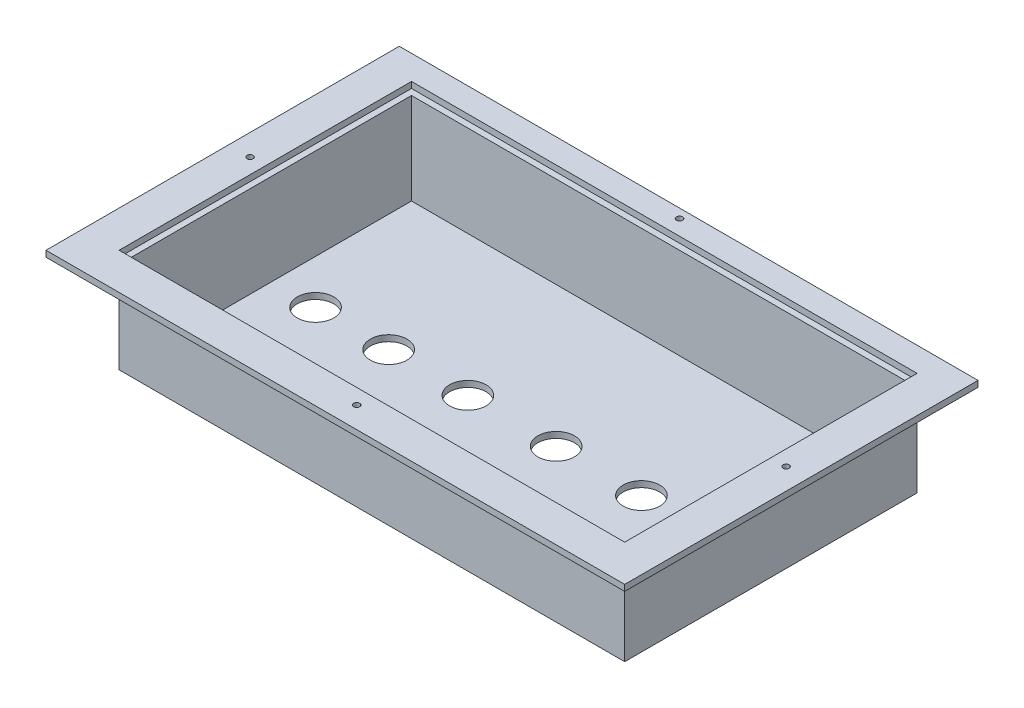
SolidWorks part; units mm, degrees
ref_plane "Front Plane" through (0, 0, 0) normal (0, 0, 1) x (1, 0, 0)
ref_plane "Top Plane" through (0, 0, 0) normal (0, 1, 0) x (1, 0, 0)
ref_plane "Right Plane" through (0, 0, 0) normal (1, 0, 0) x (0, 0, -1)
sketch "Sketch2" plane through (0, 0, 0) normal (0, 1, 0) x (1, 0, 0)
  line L1 (-83, 48) -> (83, 48)
  line L2 (-83, 48) -> (-83, -48)
  line L3 (-83, -48) -> (83, -48)
  line L4 (83, 48) -> (83, -48)
  line L5 (-83, 48) -> (83, -48) construction
  line L6 (-83, -48) -> (83, 48) construction
  line L11 (-81, 46) -> (81, -46) construction
  line L12 (-81, -46) -> (81, 46) construction
  circle A0 centre (-66.5, 0) radius 6
  circle A1 centre (-42.5, 0) radius 6
  circle A2 centre (-16.5, 0) radius 6
  circle A3 centre (12.5, 0) radius 6
  circle A4 centre (40.5, 0) radius 6
  circle A5 centre (67.0043, 4.7099) radius 4.5
  circle A6 centre (67.0043, -8.4422) radius 4.5
  circle A7 centre (67.0043, 22.9699) radius 5.5638
  point P0 (0, 0)
  point P16 (-83, 0)
  point P24 (0, 0)
  dimension "D3" = 16.5
  dimension "D8" = 92
  dimension "D1" = 166
  dimension "D2" = 96
  dimension "D4" = 40.5
  dimension "D5" = 66.5
  dimension "D6" = 95.5
  dimension "D7" = 123.5
  dimension "D9" = 162
extrude "Boss-Extrude1" add sketch "Sketch2" along normal blind 2 contours A0 | A1 | A2 | A3 | A4 | A6 | A7 | L2 L3 L4 L1 | A5
sketch "Sketch3" plane through (0, 2, 0) normal (0, 1, 0) x (1, 0, 0)
  line L1 (-81, 46) -> (81, 46)
  line L2 (-81, 46) -> (-81, -46)
  line L3 (-81, -46) -> (81, -46)
  line L4 (81, 46) -> (81, -46)
  line L5 (-81, 46) -> (81, -46) construction
  line L6 (-81, -46) -> (81, 46) construction
  line L7 (-83, 48) -> (83, 48)
  line L8 (-83, 48) -> (-83, -48)
  line L9 (-83, -48) -> (83, -48)
  line L10 (83, 48) -> (83, -48)
  line L11 (-83, 48) -> (83, -48) construction
  line L12 (-83, -48) -> (83, 48) construction
  point P0 (0, 0)
  point P6 (0, 0)
  dimension "D1" = 162
  dimension "D2" = 92
extrude "Boss-Extrude2" add sketch "Sketch3" along normal blind 30
sketch "Sketch4" plane through (0, 32, 0) normal (0, 1, 0) x (1, 0, 0)
  line L0 (-83, -48) -> (83, -48) construction
  line L1 (-95, 56) -> (95, 56)
  line L2 (-95, 56) -> (-95, -56)
  line L3 (-95, -56) -> (95, -56)
  line L4 (95, 56) -> (95, -56)
  line L5 (-95, 56) -> (95, -56) construction
  line L6 (-95, -56) -> (95, 56) construction
  line L7 (-83, 48) -> (-83, -48) construction
  line L8 (83, 48) -> (-83, 48) construction
  line L9 (83, -48) -> (83, 48) construction
  line L11 (-81, 46) -> (81, 46)
  line L12 (-81, 46) -> (-81, -46)
  line L13 (-81, -46) -> (81, -46)
  line L14 (81, 46) -> (81, -46)
  line L15 (-81, 46) -> (81, -46) construction
  line L16 (-81, -46) -> (81, 46) construction
  line L17 (-95, -56) -> (95, -56)
  line L18 (-95, -56) -> (-95, -60)
  line L19 (-95, -60) -> (95, -60)
  line L20 (95, -56) -> (95, -60)
  circle A0 centre (0, -53) radius 1
  circle A1 centre (-88, 0) radius 1
  circle A2 centre (0, 53) radius 1
  circle A3 centre (88, 0) radius 1
  point P0 (0, 0)
  point P10 (0, -48)
  point P23 (0, 0)
  line M2 (83, -48) -> (83, 48)
  line M3 (83, 48) -> (-83, 48)
  line M4 (-83, 48) -> (-83, -48)
  line M5 (-83, -48) -> (83, -48)
  dimension "D3" = 5
  dimension "D4" = 5
  dimension "D5" = 5
  dimension "D6" = 5
  dimension "D1" = 190
  dimension "D2" = 112
extrude "Boss-Extrude3" add sketch "Sketch4" along normal blind 2 separate body contours L4 L1 L2 L3 A3 A2 A1 A0 M2 M5 M4 M3 | L20 L3 L18 L19
